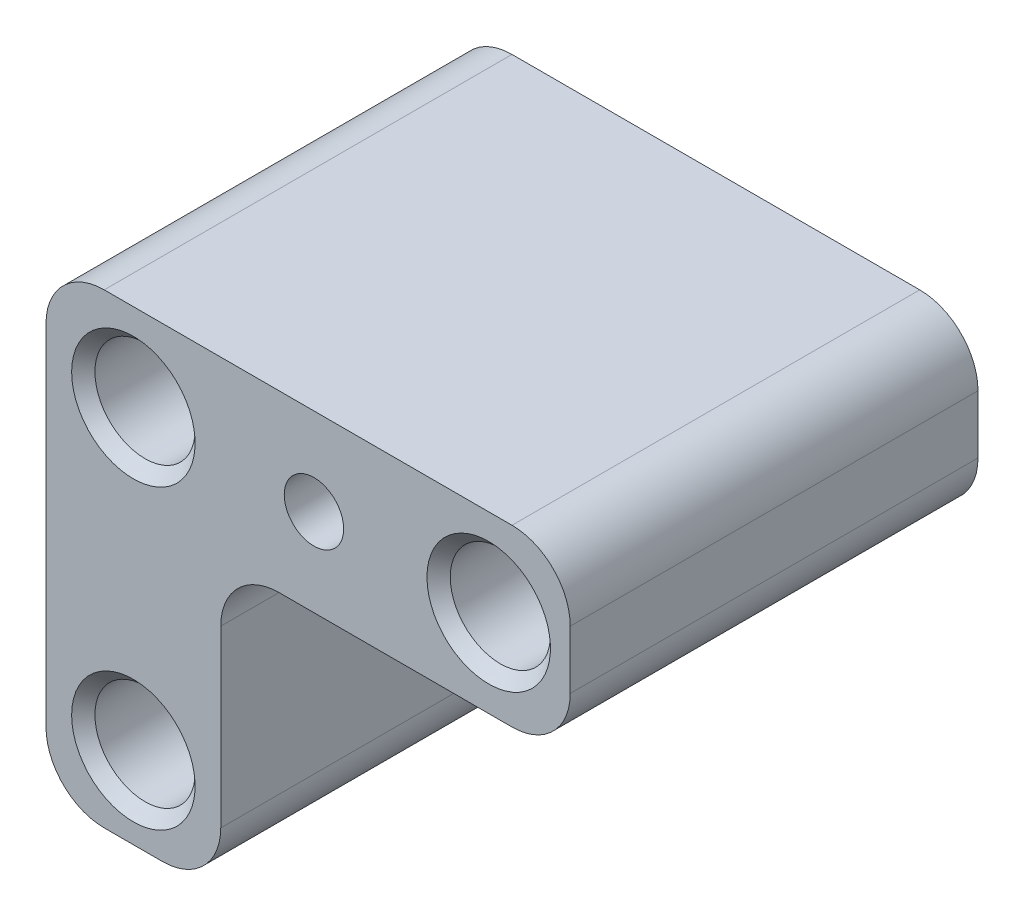
SolidWorks part; units mm, degrees
ref_plane "Front Plane" through (0, 0, 0) normal (0, 0, 1) x (1, 0, 0)
ref_plane "Top Plane" through (0, 0, 0) normal (0, 1, 0) x (1, 0, 0)
ref_plane "Right Plane" through (0, 0, 0) normal (1, 0, 0) x (0, 0, -1)
sketch "Sketch2" plane through (0, 0, 0) normal (0, 0, 1) x (1, 0, 0)
  line L1 (-311.5, 320) -> (-326.5, 320)
  line L2 (-311.5, 320) -> (-311.5, 360)
  line L3 (-311.5, 360) -> (-326.5, 360)
  line L4 (-326.5, 320) -> (-326.5, 360)
  line L5 (-311.5, 360) -> (-281.5, 360)
  line L6 (-311.5, 360) -> (-311.5, 345)
  line L7 (-311.5, 345) -> (-281.5, 345)
  line L8 (-281.5, 360) -> (-281.5, 345)
  line L10 (-281.5, 352.5) -> (-340.0828, 352.5) construction
  line L11 (-319, 320) -> (-319, 373.0529) construction
  line L12 (-303.5, 320) -> (-303.5, 373.0529) construction
  circle A0 centre (-319, 327) radius 2.55
  circle A1 centre (-288.5, 352.5) radius 2.55
  circle A2 centre (-319, 352.5) radius 2.55
  dimension "D7" = 5.1
  dimension "D8" = 5.1
  dimension "D11" = 0
  dimension "D13" = 5.1
  dimension "D1" = 15
  dimension "D2" = 15
  dimension "D4" = 30
  dimension "D5" = 40
  dimension "D9" = 7
  dimension "D10" = 7
  dimension "D12" = 0
extrude "Boss-Extrude1" add sketch "Sketch2" along normal blind 35 contours A1 | A2 | A0 | L2 L1 L4 L3 | L6 L7 L8 L5
sketch "Sketch3" plane through (0, 0, 35) normal (0, 0, 1) x (1, 0, 0)
  circle A0 centre (-319, 352.5) radius 4.3
  circle A1 centre (-319, 327) radius 4.3
  circle A2 centre (-288.5, 352.5) radius 4.3
  dimension "D1" = 8.6
extrude "Cut-Extrude1" cut sketch "Sketch3" against normal blind 29.6
sketch "Sketch4" plane through (0, 0, 0) normal (0, 0, -1) x (-1, 0, 0)
  line L0 (281.5, 352.5) -> (328.8705, 352.5)
  line L1 (281.5, 360) -> (281.5, 345) construction
  circle A0 centre (303.5, 352.5) radius 4.3
  circle A1 centre (288.5, 352.5) radius 2.55 construction
  dimension "D1" = 8.6
  dimension "D2" = 15
extrude "Cut-Extrude2" cut sketch "Sketch4" against normal blind 29.6 contours A0
sketch "Sketch5" plane through (0, 0, 29.6) normal (0, 0, -1) x (-1, 0, 0)
  circle A0 centre (303.5, 352.5) radius 2.55
  dimension "D1" = 5.1
extrude "Cut-Extrude3" cut sketch "Sketch5" against normal blind 29.6
fillet "Fillet1" radius 5 6 edges at (-281.5, 360, 17.5) (-281.5, 345, 17.5) (-311.5, 345, 17.5) (-311.5, 320, 17.5) (-326.5, 320, 17.5) (-326.5, 360, 17.5)
chamfer "Chamfer1" distance 1 angle 45 4 edges at (-284.2, 352.5, 35) (-314.7, 352.5, 35) (-314.7, 327, 35) (-307.8, 352.5, 0)
